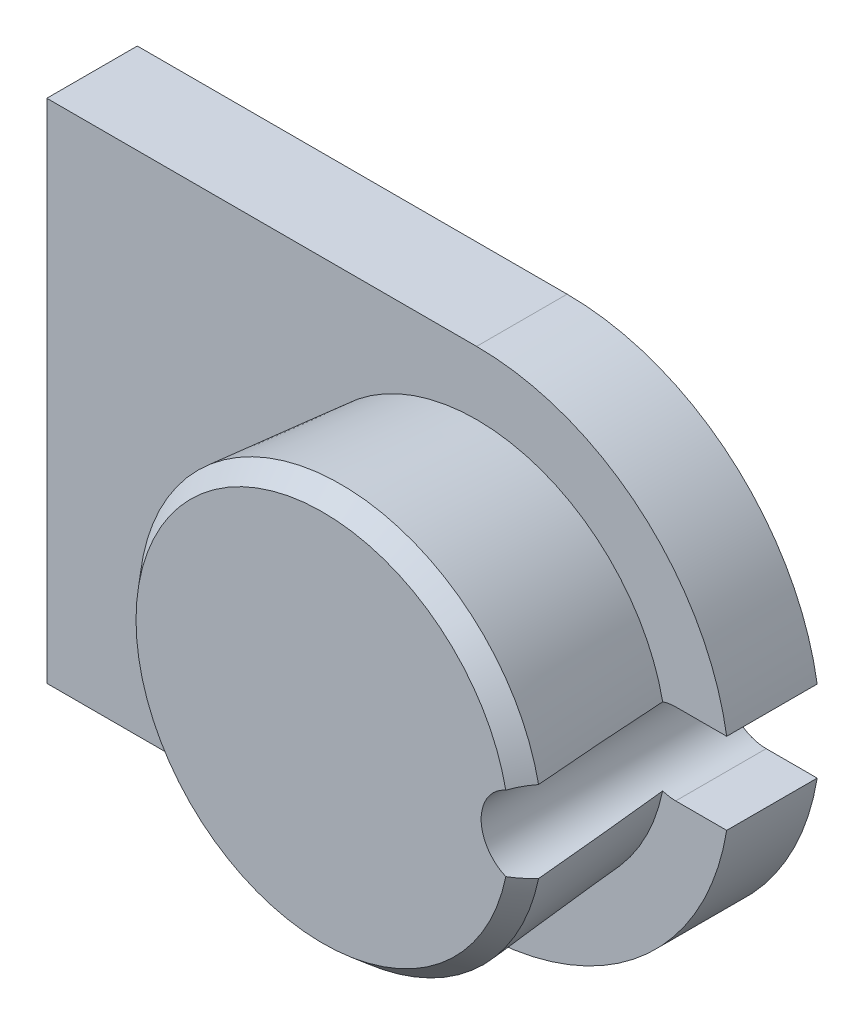
SolidWorks part; units mm, degrees
ref_plane "Ebene vorne" through (0, 0, 0) normal (0, 0, 1) x (1, 0, 0)
ref_plane "Ebene oben" through (0, 0, 0) normal (0, 1, 0) x (1, 0, 0)
ref_plane "Ebene rechts" through (0, 0, 0) normal (1, 0, 0) x (0, 0, -1)
ref_plane "Ebene1" through (0, 0, 4.2) normal (0, 0, 1) x (1, 0, 0)
sketch "Skizze2" plane through (0, 0, 4.2) normal (0, 0, 1) x (1, 0, 0)
  line L0 (60.75, 19.8) -> (65.5, 19.8)
  line L1 (65.5, 14.2) -> (60.75, 14.2)
  line L2 (60.75, 14.2) -> (60.75, 19.8)
  arc A0 (65.5, 19.8) -> (65.5, 14.2) centre (65.5, 17) cw
  dimension "D3" = 2.8
  dimension "D1" = 65.5
  dimension "D2" = 17
  dimension "D4" = 60.75
extrude "Aufsatz-Linear austragen1" add sketch "Skizze2" against normal blind 1
sketch "Skizze3" plane through (0, 0, 4.2) normal (0, 0, 1) x (1, 0, 0)
  circle A0 centre (65.5, 17) radius 2.1
  arc A1 (65.5, 14.2) -> (65.5, 19.8) centre (65.5, 17) ccw construction
  dimension "D1" = 4.2
extrude "Aufsatz-Linear austragen2" add sketch "Skizze3" along normal blind 1.7 draft 5 draft outward yes
chamfer "Fase1" distance 0.2 angle 45 1 edges at (67.7487, 17, 5.9)
sketch "Skizze4" plane through (0, 0, 4.2) normal (0, 0, 1) x (1, 0, 0)
  line L0 (69.3246, 17) -> (67.7, 17) construction
  line L1 (69.3246, 16.55) -> (67.7, 16.55)
  line L2 (69.3246, 17.45) -> (67.7, 17.45)
  line L3 (65.5, 19.0641) -> (65.5, 14.9359) construction
  arc A0 (69.3246, 16.55) -> (69.3246, 17.45) centre (69.3246, 17) ccw
  arc A1 (67.7, 17.45) -> (67.7, 16.55) centre (67.7, 17) ccw
  circle A2 centre (65.5, 17) radius 2.0641 construction
  point P2 (68.5123, 17)
  point P12 (65.5, 17)
  dimension "D1" = 0.45
  dimension "D2" = 2.2
extrude "Schnitt-Linear austragen1" cut sketch "Skizze4" against normal through all both and the other way through all
other "Körper speichern1"
